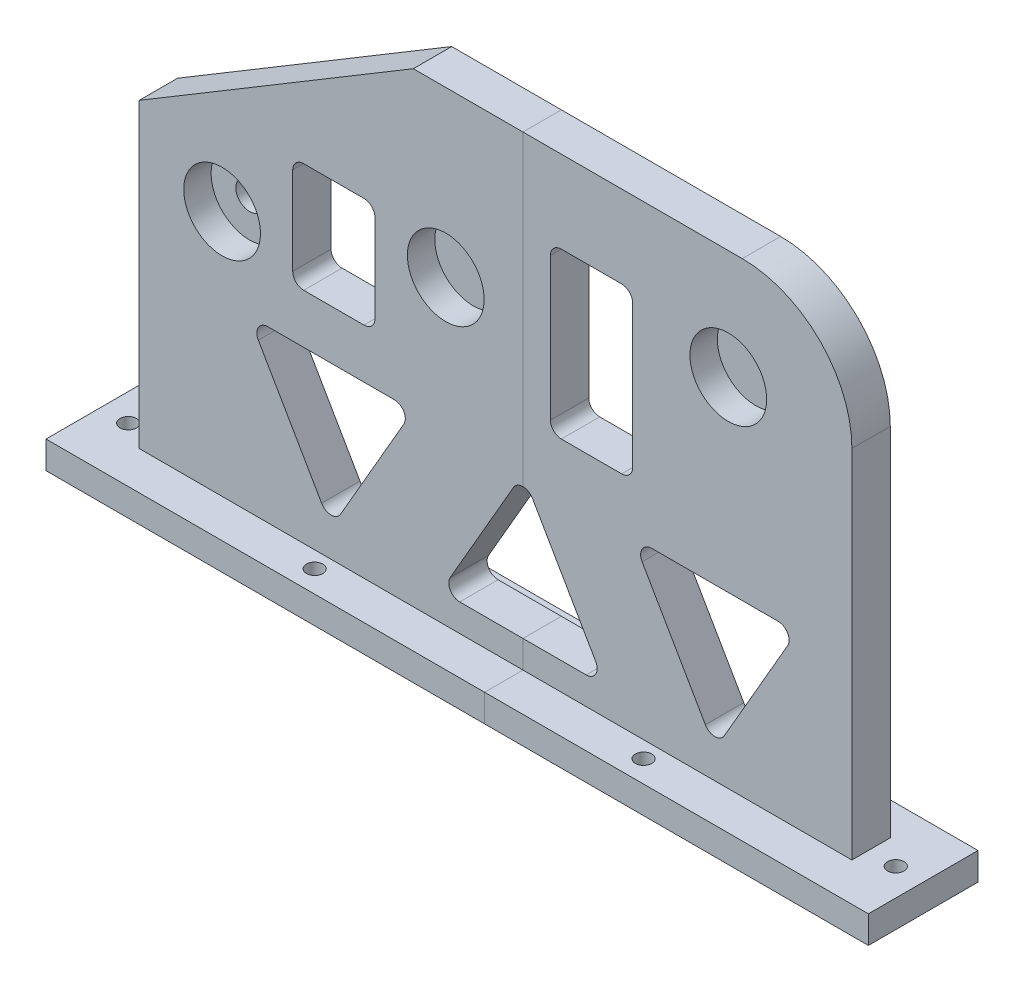
SolidWorks part; units mm, degrees
ref_plane "前视基准面" through (0, 0, 0) normal (0, 0, 1) x (1, 0, 0)
ref_plane "上视基准面" through (0, 0, 0) normal (0, 1, 0) x (1, 0, 0)
ref_plane "右视基准面" through (0, 0, 0) normal (1, 0, 0) x (0, 0, -1)
other "Configuration Table"
sketch "草图3" plane through (0, 0, 0) normal (0, 0, 1) x (1, 0, 0)
  line L0 (0, 0) -> (130, 0)
  line L2 (130, 90) -> (0, 90)
  line L4 (0, 0) -> (0, 90)
  line L5 (130, 90) -> (130, 0)
  dimension "D1" = 90
  dimension "D2" = 130
extrude "凸台-拉伸2" add sketch "草图3" along normal blind 7
hole_wizard "Ø14.0 (14) 直径孔1" positions "草图19" profile "草图20" hole size "Ø5.0" standard "GB" end condition through all
sketch "草图19" plane through (0, 0, 0) normal (0, 0, -1) x (-1, 0, 0)
  point P6 (-15.1208, 50)
sketch "草图20" plane through (15.1208, 50, 0) normal (1, 0, 0) x (0, 1, 0)
  line L0 (0, 0) -> (0, 7)
  line L1 (0, 7) -> (2.5, 7)
  line L2 (2.5, 7) -> (2.5, 0)
  line L5 (2.5, 0) -> (0, 0)
  line L11 (0, -6.35) -> (0, 107.95) construction
  dimension "通孔孔直径" = 5
  dimension "通孔孔深度" = 7
sketch "草图22" plane through (0, 0, 7) normal (0, 0, 1) x (1, 0, 0)
  circle A0 centre (15.1208, 50) radius 7
  circle A1 centre (55.913, 60) radius 7
  circle A2 centre (107.4518, 70) radius 7
  dimension "D1" = 14
  dimension "D2" = 14
  dimension "D3" = 14
extrude "切除-拉伸4" cut sketch "草图22" against normal blind 5
chamfer "倒角2" distance 50 distance2 30 1 edges at (0, 90, 3.5)
fillet "圆角3" radius 20 1 edges at (130, 90, 3.5)
sketch "草图25" plane through (0, 0, 0) normal (0, -1, 0) x (1, 0, 0)
  line L0 (-10, 14) -> (-10, -6)
  line L1 (-10, -6) -> (140, -6)
  line L2 (140, -6) -> (140, 14)
  line L3 (140, 14) -> (-10, 14)
  line L5 (0, 7) -> (130, 7) construction
  line L6 (0, 7) -> (0, 0) construction
  dimension "D1" = 20
  dimension "D2" = 7
  dimension "D3" = 150
  dimension "D4" = 10
extrude "凸台-拉伸3" add sketch "草图25" against normal blind 5
sketch "草图26" plane through (0, 5, 0) normal (0, 1, 0) x (1, 0, 0)
  line L0 (-10, -14) -> (-10, 6) construction
  line L1 (140, -14) -> (-10, -14) construction
  line L3 (140, 6) -> (140, -14) construction
  line L4 (0, 0) -> (130, 0) construction
  line L5 (50, -7) -> (0, -7) construction
  line L6 (110, -7) -> (50, -7) construction
  circle A0 centre (-5, -4) radius 1.5
  circle A1 centre (135, -4) radius 1.5
  circle A2 centre (35, -10) radius 1.5
  circle A3 centre (95, -10) radius 1.5
  circle A4 centre (95, 3) radius 1.5
  circle A5 centre (35, 3) radius 1.5
  dimension "D1" = 3
  dimension "D2" = 3
  dimension "D7" = 3
  dimension "D8" = 3
  dimension "D9" = 3
  dimension "D10" = 3
  dimension "D3" = 5
  dimension "D4" = 10
  dimension "D5" = 10
  dimension "D6" = 5
  dimension "D11" = 3
  dimension "D12" = 3
  dimension "D13" = 3
  dimension "D14" = 3
  dimension "D15" = 60
  dimension "D16" = 60
  dimension "D17" = 45
extrude "切除-拉伸5" cut sketch "草图26" against normal through all
sketch "草图27" plane through (0, 0, 7) normal (0, 0, 1) x (1, 0, 0)
  line L0 (20, 35.9808) -> (50, 35.9808)
  line L1 (50, 35.9808) -> (35, 10)
  line L2 (35, 10) -> (20, 35.9808)
  line L3 (55, 10) -> (85, 10)
  line L4 (85, 10) -> (70, 35.9808)
  line L5 (70, 35.9808) -> (55, 10)
  line L9 (90, 35.9808) -> (120, 35.9808)
  line L10 (120, 35.9808) -> (105, 10)
  line L11 (105, 10) -> (90, 35.9808)
  line L12 (0, 5) -> (130, 5) construction
  line L13 (0, 60) -> (0, 5) construction
  dimension "D1" = 30
  dimension "D2" = 30
  dimension "D3" = 30
  dimension "D4" = 20
  dimension "D5" = 20
  dimension "D6" = 5
  dimension "D7" = 20
  dimension "D8" = 30
  dimension "D9" = 30
  dimension "D10" = 30
extrude "切除-拉伸6" cut sketch "草图27" against normal up to next
fillet "圆角4" radius 2 9 edges at (90, 35.9808, 3.5) (120, 35.9808, 3.5) (105, 10, 3.5) (70, 35.9808, 3.5) (55, 10, 3.5) (85, 10, 3.5) (20, 35.9808, 3.5) (50, 35.9808, 3.5) (35, 10, 3.5)
sketch "草图28" plane through (0, 0, 7) normal (0, 0, 1) x (1, 0, 0)
  line L0 (110, 90) -> (50, 90) construction
  line L1 (75, 45) -> (90, 45)
  line L2 (75, 45) -> (75, 75)
  line L3 (75, 75) -> (90, 75)
  line L4 (90, 45) -> (90, 75)
  line L5 (130, 5) -> (130, 70) construction
  line L6 (0, 60) -> (0, 5) construction
  line L7 (28, 45) -> (43, 45)
  line L8 (28, 45) -> (28, 65)
  line L9 (28, 65) -> (43, 65)
  line L10 (43, 45) -> (43, 65)
  dimension "D1" = 30
  dimension "D2" = 15
  dimension "D3" = 15
  dimension "D4" = 40
  dimension "D5" = 15
  dimension "D6" = 20
  dimension "D7" = 28
  dimension "D8" = 25
extrude "切除-拉伸7" cut sketch "草图28" against normal through all
fillet "圆角5" radius 2 8 edges at (28, 45, 3.5) (43, 65, 3.5) (28, 65, 3.5) (43, 45, 3.5) (75, 45, 3.5) (90, 45, 3.5) (75, 75, 3.5) (90, 75, 3.5)
ref_plane "基准面1" through (70, 0, 0) normal (1, 0, 0) x (0, 0, -1)
split "分割1" trim tools "基准面1" bodies to split 121 resulting bodies 122 123
